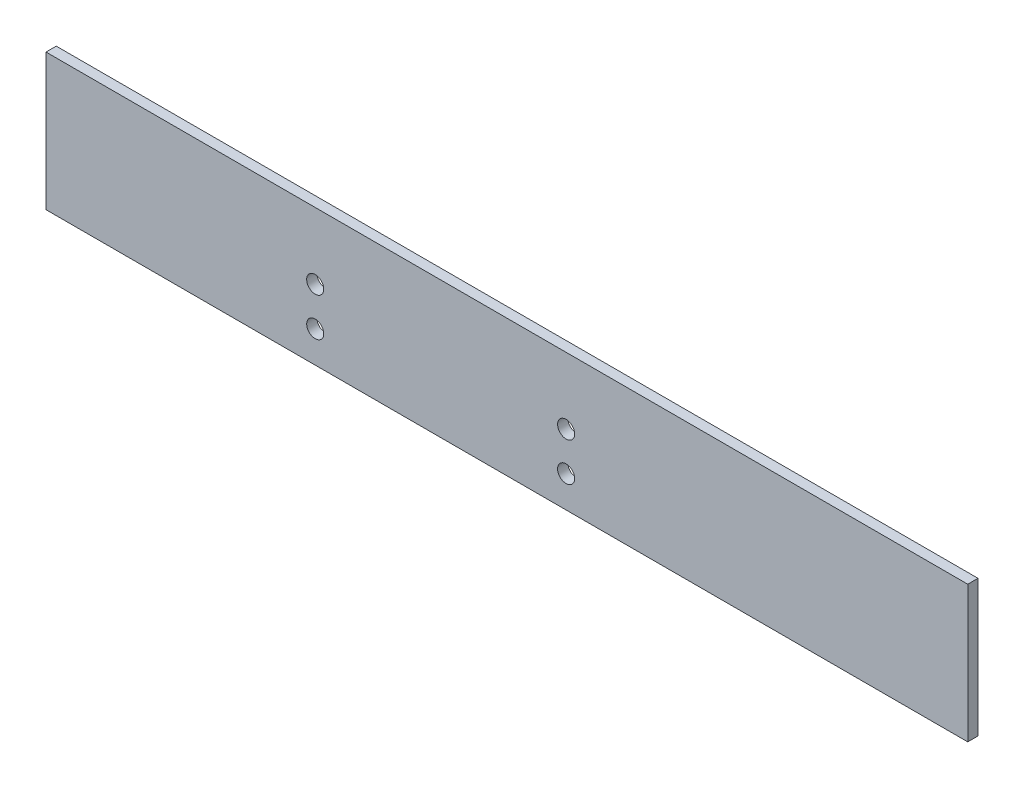
SolidWorks part; units mm, degrees
ref_plane "Front Plane" through (0, 0, 0) normal (0, 0, 1) x (1, 0, 0)
ref_plane "Top Plane" through (0, 0, 0) normal (0, 1, 0) x (1, 0, 0)
ref_plane "Right Plane" through (0, 0, 0) normal (1, 0, 0) x (0, 0, -1)
sketch "Esquisse1" plane through (0, 0, 0) normal (0, 0, 1) x (1, 0, 0)
  line L1 (0, 0) -> (270, 0)
  line L2 (0, 0) -> (0, -40)
  line L3 (0, -40) -> (270, -40)
  line L4 (270, 0) -> (270, -40)
  circle A0 centre (78.8546, -19.5) radius 2.5
  circle A1 centre (78.8546, -30.8) radius 2.5
  circle A2 centre (152.3533, -19.5) radius 2.5
  circle A3 centre (152.3533, -30.8) radius 2.5
  dimension "D3" = 5
  dimension "D4" = 5
  dimension "D5" = 5
  dimension "D6" = 5
  dimension "D1" = 270
  dimension "D2" = 40
extrude "Boss.-Extru.1" add sketch "Esquisse1" along normal blind 3
